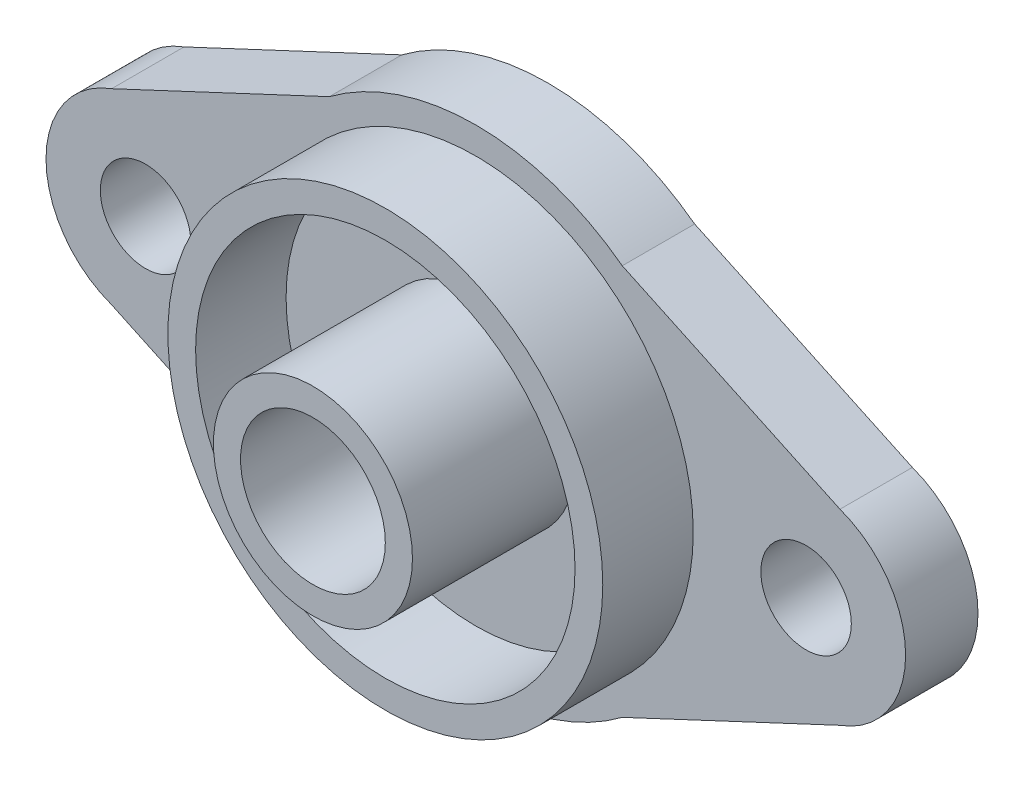
SolidWorks part; units mm, degrees
material "Cast Alloy Steel"
ref_plane "Plano frontal" through (0, 0, 0) normal (0, 0, 1) x (1, 0, 0)
ref_plane "Plano superior" through (0, 0, 0) normal (0, 1, 0) x (1, 0, 0)
ref_plane "Plano direito" through (0, 0, 0) normal (1, 0, 0) x (0, 0, -1)
sketch "Esboço1" plane through (0, 0, 0) normal (0, 0, 1) x (1, 0, 0)
  line L0 (-18.25, 0) -> (18.25, 0) construction
  line L1 (0, 0) -> (0, 13.5) construction
  line L2 (-20.124, 5.1709) -> (-8.0937, 10.8047)
  line L3 (-18.25, 0) -> (-23.75, 0) construction
  line L4 (-20.124, -5.1709) -> (-8.0937, -10.8047)
  line L5 (20.124, -5.1709) -> (8.0937, -10.8047)
  line L6 (20.124, 5.1709) -> (8.0937, 10.8047)
  circle A0 centre (0, 0) radius 4
  circle A1 centre (-18.25, 0) radius 2.5
  circle A2 centre (18.25, 0) radius 2.5
  arc A4 (-20.124, 5.1709) -> (-20.124, -5.1709) centre (-18.25, 0) ccw
  arc A5 (8.0937, 10.8047) -> (-8.0937, 10.8047) centre (0, 0) ccw
  arc A6 (8.0937, -10.8047) -> (-8.0937, -10.8047) centre (0, 0) cw
  arc A7 (20.124, 5.1709) -> (20.124, -5.1709) centre (18.25, 0) cw
  dimension "D1" = 5
  dimension "D2" = 5
  dimension "D4" = 8
  dimension "D6" = 11
  dimension "D3" = 36.5
extrude "Ressalto-extrusão1" add sketch "Esboço1" along normal blind 4
sketch "Esboço2" plane through (0, 0, 4) normal (0, 0, 1) x (1, 0, 0)
  circle A0 centre (0, 0) radius 12.0157
  circle A1 centre (0, 0) radius 10.4838
extrude "Ressalto-extrusão2" add sketch "Esboço2" along normal blind 5
sketch "Esboço3" plane through (0, 0, 4) normal (0, 0, 1) x (1, 0, 0)
  circle A0 centre (0, 0) radius 4
  circle A1 centre (0, 0) radius 5.5
  dimension "D1" = 11
extrude "Ressalto-extrusão3" add sketch "Esboço3" along normal blind 9
